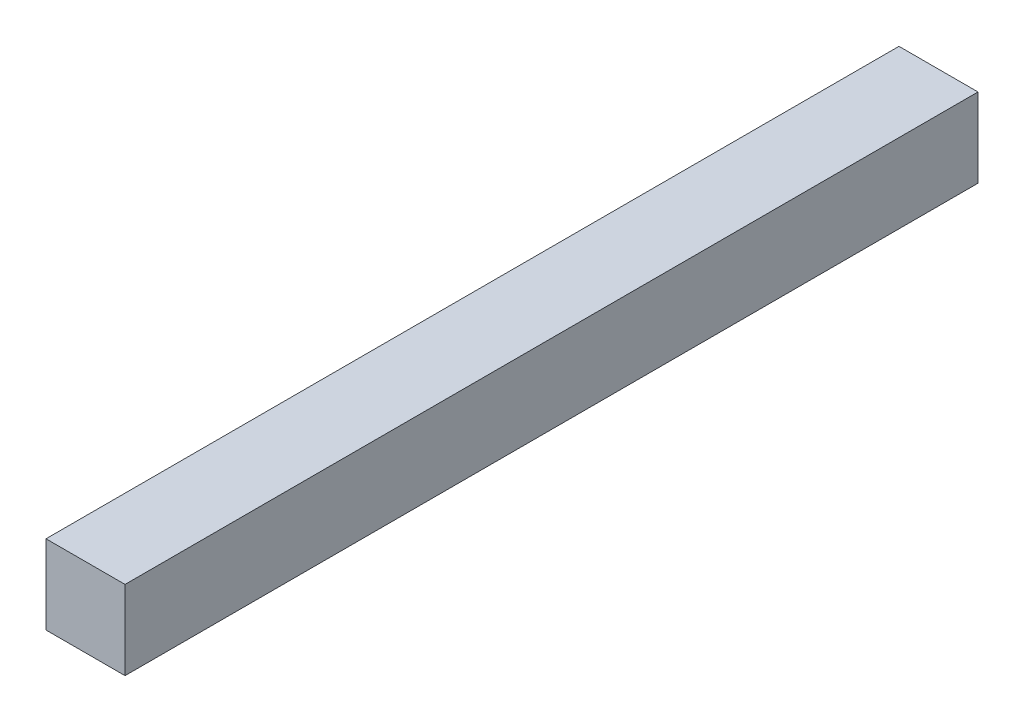
SolidWorks part; units mm, degrees
ref_plane "Front Plane" through (0, 0, 0) normal (0, 0, 1) x (1, 0, 0)
ref_plane "Top Plane" through (0, 0, 0) normal (0, 1, 0) x (1, 0, 0)
ref_plane "Right Plane" through (0, 0, 0) normal (1, 0, 0) x (0, 0, -1)
sketch "Sketch1" plane through (0, 0, 0) normal (0, 0, 1) x (1, 0, 0)
  line L1 (-1.39, 1.39) -> (1.39, 1.39)
  line L2 (-1.39, 1.39) -> (-1.39, -1.39)
  line L3 (-1.39, -1.39) -> (1.39, -1.39)
  line L4 (1.39, 1.39) -> (1.39, -1.39)
  line L5 (-1.39, 1.39) -> (1.39, -1.39) construction
  line L6 (-1.39, -1.39) -> (1.39, 1.39) construction
  point P0 (0, 0)
  dimension "D1" = 2.78
  dimension "D2" = 2.78
extrude "Boss-Extrude1" add sketch "Sketch1" along normal mid plane 30
equation "\"shaft inner diameter\"= 15mm "
equation "\"shaft outer diameter\"= 20mm "
equation "\"keyway_height\" = 1.39mm "
equation "\"keyway_width\" = 2.78mm "
equation "\"keyway_length\" = 30mm "
equation "\"steering column length\" = 555mm "
equation "\"steering wheel bolt width\" = 6mm "
equation "\"steering wheel bolt length\" = 40mm "
equation "\"bushing length\" = 40mm "
equation "\"bushing thickness\" = 3mm "
equation "\"u_joint clearance\" = 30mm "
equation "\"u_joint thickness\" = 7.5mm "
equation "\"horizontal shaft length\" = 90mm "
equation "\"short_bearing_outer_width\" = 10mm "
equation "\"column bushing diameter\" = \"primary shaft small diameter\" + 4 "
equation "\"column bushing distance\" = \"steering column length\"/4 "
equation "\"pinion width\" = 26.5mm "
equation "\"number of teeth\" = 18mm "
equation "\"D1@Sketch1\"=\"keyway_width\""
equation "\"D2@Sketch1\"=\"keyway_height\"*2"
equation "\"D1@Boss-Extrude1\"=\"keyway_length\""
equation "\"column angle\" = 45deg "
equation "\"wheel base\" = 1561mm "
equation "\"track\" = 1354mm "
equation "\"turning radius\" = 2000mm "
equation "\"turn to lock\" = 0.75mm "
equation "\"steering arm length\" = 100mm "
equation "\"primary shaft small diameter\" = 16mm "
equation "\"primary shaft large diameter\" = 24mm "
equation "\"secondary shaft small diameter\" = 16mm "
equation "\"secondary shaft large diameter\" = 25mm "
equation "\"pin hole diameter\" = 10mm "
equation "\"rack hole to hole\" = 500mm "
equation "\"rack length\" = \"rack hole to hole\" + \"pin hole diameter\"*2 "
equation "\"max turning angle\" = atn(\"wheel base\" / (\"turning radius\" - 0.5 * \"track\")) "
equation "\"max travel\" = 2 * \"steering arm length\" * sin(0.5 * \"max turning angle\") "
equation "\"pitch diameter\" = \"max travel\"/(pi * \"turn to lock\") "
equation "\"pressure angle\" = 20deg "
equation "\"module\" = \"pitch diameter\" / \"number of teeth\" "
equation "\"tie rod length\" = 305mm "
equation "\"tie rod inner diameter\" = 6.6mm "
equation "\"tie rod outer diameter\" = 8.1mm "
